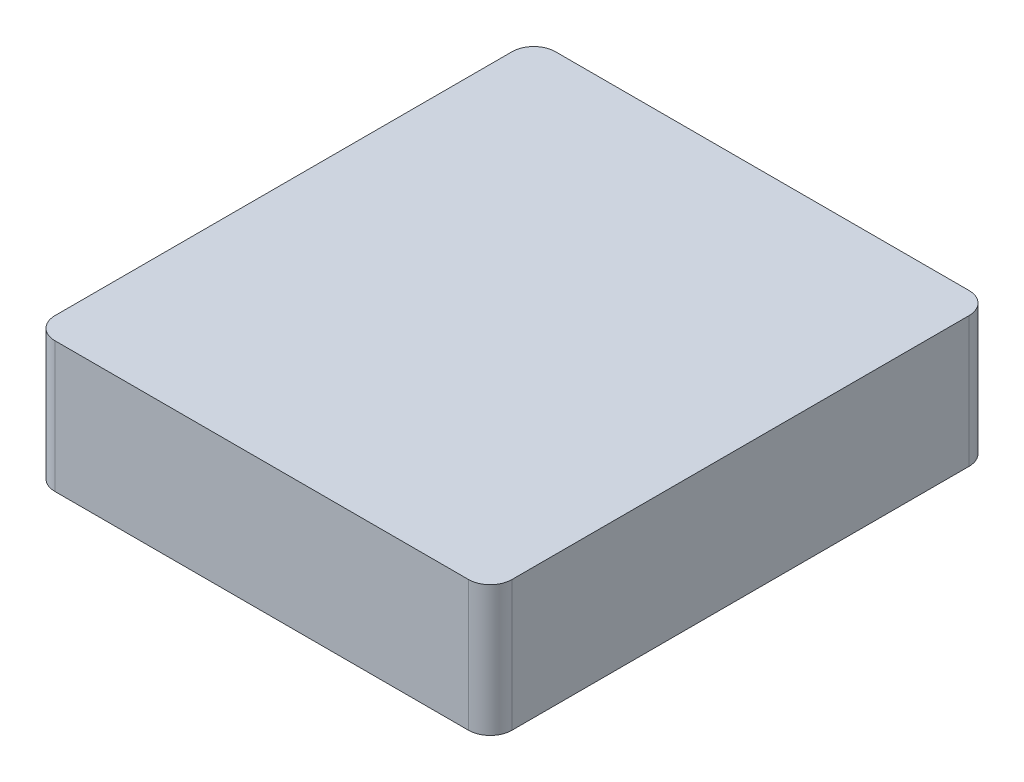
SolidWorks part; units mm, degrees
ref_plane "Front Plane" through (0, 0, 0) normal (0, 0, 1) x (1, 0, 0)
ref_plane "Top Plane" through (0, 0, 0) normal (0, 1, 0) x (1, 0, 0)
ref_plane "Right Plane" through (0, 0, 0) normal (1, 0, 0) x (0, 0, -1)
sketch "Sketch3" plane through (0, 0, 0) normal (0, 1, 0) x (1, 0, 0)
  line L1 (-10.5, 11.5) -> (10.5, 11.5)
  line L2 (-10.5, 11.5) -> (-10.5, -11.5)
  line L3 (-10.5, -11.5) -> (10.5, -11.5)
  line L4 (10.5, 11.5) -> (10.5, -11.5)
  line L5 (-10.5, 11.5) -> (10.5, -11.5) construction
  line L6 (-10.5, -11.5) -> (10.5, 11.5) construction
  point P0 (0, 0)
  dimension "D1" = 23
  dimension "D2" = 21
extrude "Boss-Extrude2" add sketch "Sketch3" along normal blind 6
fillet "Fillet1" radius 1 4 edges at (-10.5, 3, -11.5) (10.5, 3, -11.5) (10.5, 3, 11.5) (-10.5, 3, 11.5)
